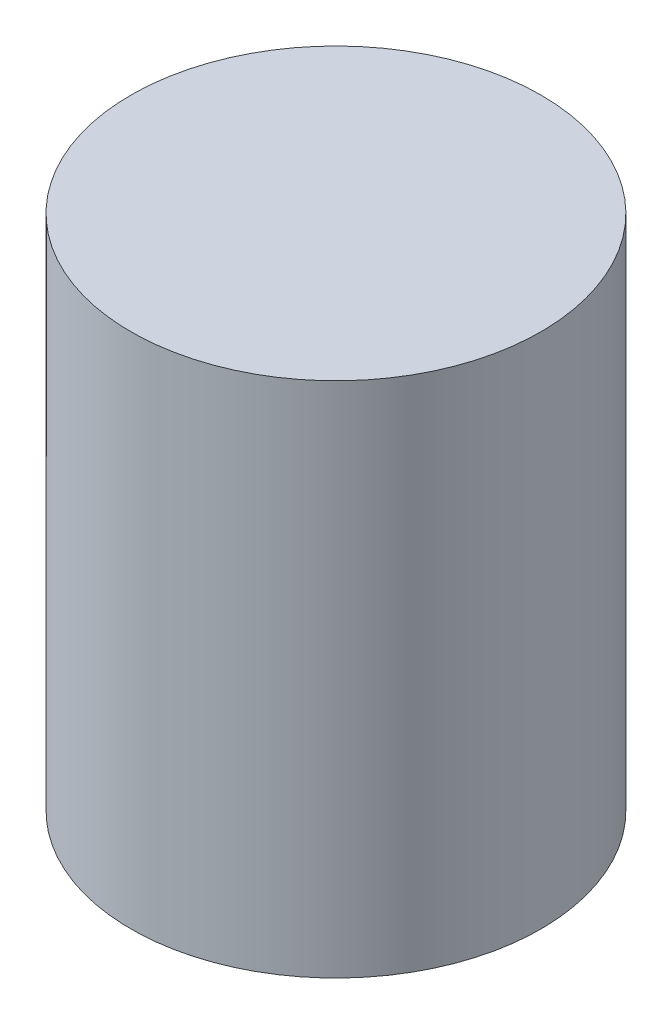
SolidWorks part; units mm, degrees
material "6061-T6 (SS)"
ref_plane "Piano frontale" through (0, 0, 0) normal (0, 0, 1) x (1, 0, 0)
ref_plane "Piano superiore" through (0, 0, 0) normal (0, 1, 0) x (1, 0, 0)
ref_plane "Piano destro" through (0, 0, 0) normal (1, 0, 0) x (0, 0, -1)
sketch "Schizzo1" plane through (0, 0, 0) normal (0, 0, 1) x (1, 0, 0)
  line L0 (0, 0) -> (0, 23.6846) construction
  line L1 (-14, 0) -> (-14, 35)
  line L2 (-14, 35) -> (0, 35)
  line L3 (0, 35) -> (0, 40)
  line L4 (0, 40) -> (-20, 40)
  line L5 (-20, 40) -> (-20, 0)
  line L6 (-20, 0) -> (-14, 0)
  line L7 (-20, 0) -> (-20, -10.4579)
  line L8 (-20, -10.4579) -> (-18, -10.4579)
  line L9 (-18, 0) -> (-18, -12) construction
  line L10 (-18, -10.4579) -> (-18, 0)
  line L11 (-18, 0) -> (-18, -12) construction
  dimension "D1" = 28
  dimension "D2" = 40
  dimension "D3" = 5
  dimension "D4" = 35
revolve "Rivoluzione1" add sketch "Schizzo1" angle 360 about L0
